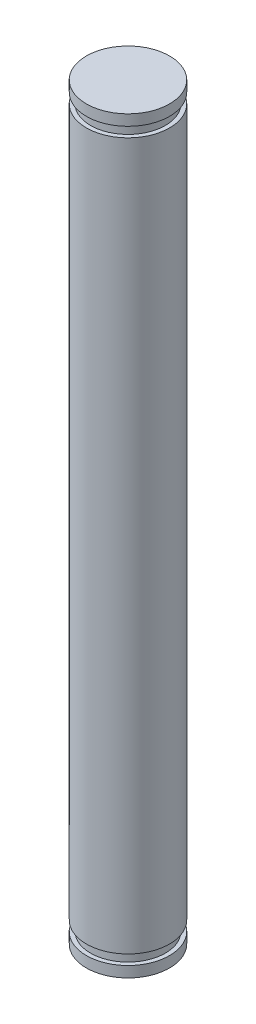
SolidWorks part; units mm, degrees
ref_plane "前视基准面" through (0, 0, 0) normal (0, 0, 1) x (1, 0, 0)
ref_plane "上视基准面" through (0, 0, 0) normal (0, 1, 0) x (1, 0, 0)
ref_plane "右视基准面" through (0, 0, 0) normal (1, 0, 0) x (0, 0, -1)
sketch "草图1" plane through (0, 0, 0) normal (0, 0, 1) x (1, 0, 0)
  line L0 (0, 0) -> (-5, 0)
  line L1 (-5, 0) -> (-5, 1.3)
  line L2 (-5, 1.3) -> (-4.5, 1.3)
  line L3 (-4.5, 1.3) -> (-4.5, 2.5)
  line L4 (-4.5, 2.5) -> (-5, 2.5)
  line L5 (-5, 2.5) -> (-5, 87.5)
  line L6 (-5, 87.5) -> (-4.5, 87.5)
  line L7 (-4.5, 87.5) -> (-4.5, 88.7)
  line L8 (-4.5, 88.7) -> (-5, 88.7)
  line L9 (-5, 88.7) -> (-5, 90)
  line L10 (-5, 90) -> (0, 90)
  line L11 (0, 90) -> (0, 0) construction
  line L12 (0, 0) -> (0, 90)
revolve "旋转1" add sketch "草图1" angle 360 about L11
